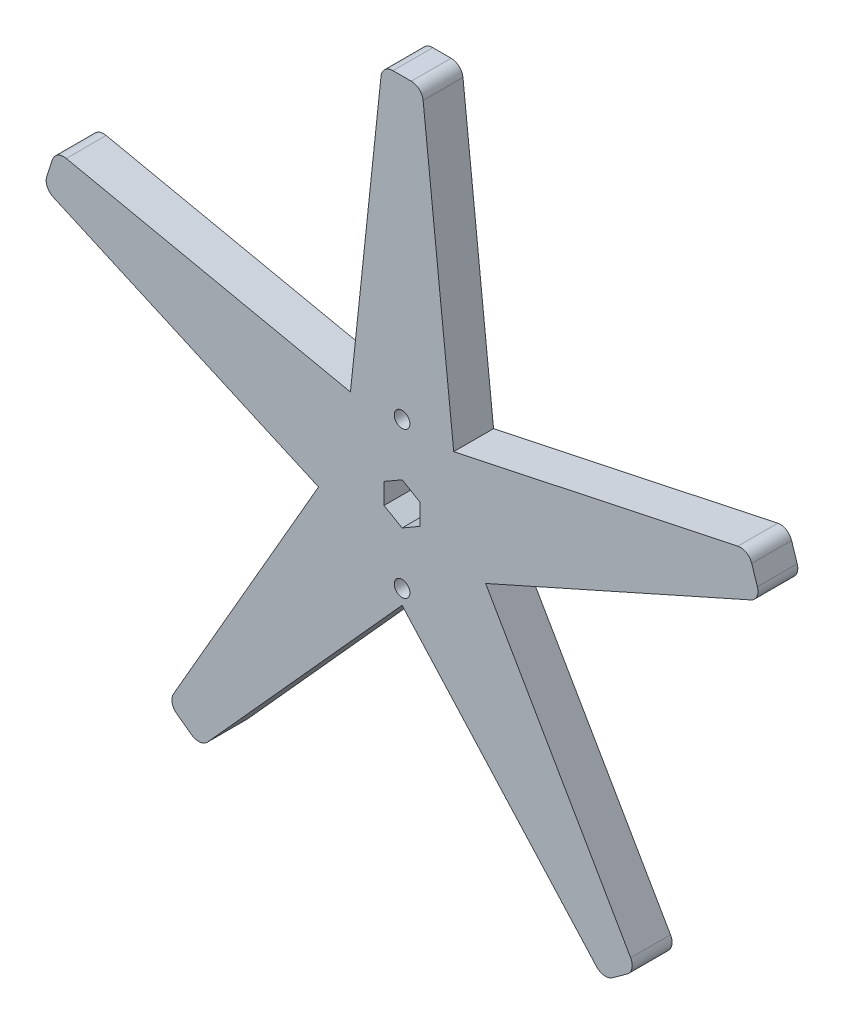
SolidWorks part; units mm, degrees
ref_plane "Front Plane" through (0, 0, 0) normal (0, 0, 1) x (1, 0, 0)
ref_plane "Top Plane" through (0, 0, 0) normal (0, 1, 0) x (1, 0, 0)
ref_plane "Right Plane" through (0, 0, 0) normal (1, 0, 0) x (0, 0, -1)
sketch "Sketch1" plane through (0, 0, 0) normal (0, 0, 1) x (1, 0, 0)
  line L0 (0, 41.9404) -> (0, 194.3404) construction
  line L1 (0, 41.9404) -> (0, 4.742) construction
  line L2 (0, 0) -> (0, 4.742) construction
  line L3 (0, 4.742) -> (0, 0) construction
  line L5 (0, -6.65) -> (5.7591, -3.325)
  line L6 (5.7591, -3.325) -> (5.7591, 3.325)
  line L7 (0, 194.3404) -> (0, 41.9404) construction
  line L8 (-2.922, 118.1404) -> (2.922, 118.1404)
  line L9 (-6.7109, 114.7315) -> (-16.458, 22.6525)
  line L10 (6.7109, 114.7315) -> (16.458, 22.6525)
  line L11 (-16.458, 22.6525) -> (0, 0) construction
  line L12 (0, 0) -> (16.458, 22.6525) construction
  line L13 (107.0424, 41.8364) -> (16.458, 22.6525)
  line L14 (111.4552, 39.2864) -> (113.2612, 33.7284)
  line L15 (111.1899, 29.0716) -> (26.6296, -8.6525)
  line L16 (72.8667, -88.8752) -> (26.6296, -8.6525)
  line L17 (71.8052, -93.8601) -> (67.0772, -97.2951)
  line L18 (62.0083, -96.7643) -> (0, -28)
  line L19 (-62.0083, -96.7643) -> (0, -28)
  line L20 (-67.0772, -97.2951) -> (-71.8052, -93.8601)
  line L21 (-72.8667, -88.8752) -> (-26.6296, -8.6525)
  line L22 (-111.1899, 29.0716) -> (-26.6296, -8.6525)
  line L23 (-113.2612, 33.7284) -> (-111.4552, 39.2864)
  line L24 (-107.0424, 41.8364) -> (-16.458, 22.6525)
  line L25 (5.7591, 3.325) -> (0, 6.65)
  line L26 (0, 6.65) -> (-5.7591, 3.325)
  line L27 (-5.7591, 3.325) -> (-5.7591, -3.325)
  line L28 (-5.7591, -3.325) -> (0, -6.65)
  circle A0 centre (0, 0) radius 28 construction
  arc A1 (6.7109, 114.7315) -> (2.922, 118.1404) centre (2.922, 114.3304) ccw
  arc A2 (-6.7109, 114.7315) -> (-2.922, 118.1404) centre (-2.922, 114.3304) cw
  arc A3 (107.0424, 41.8364) -> (111.4552, 39.2864) centre (107.8317, 38.109) cw
  arc A4 (111.1899, 29.0716) -> (113.2612, 33.7284) centre (109.6376, 32.551) ccw
  arc A5 (72.8667, -88.8752) -> (71.8052, -93.8601) centre (69.5657, -90.7777) cw
  arc A6 (62.0083, -96.7643) -> (67.0772, -97.2951) centre (64.8378, -94.2128) ccw
  arc A7 (-62.0083, -96.7643) -> (-67.0772, -97.2951) centre (-64.8378, -94.2128) cw
  arc A8 (-72.8667, -88.8752) -> (-71.8052, -93.8601) centre (-69.5657, -90.7777) ccw
  arc A9 (-111.1899, 29.0716) -> (-113.2612, 33.7284) centre (-109.6376, 32.551) cw
  arc A10 (-107.0424, 41.8364) -> (-111.4552, 39.2864) centre (-107.8317, 38.109) ccw
  circle A11 centre (0, 0) radius 5.7591 construction
  circle A12 centre (0, 23.3412) radius 2.5
  circle A13 centre (0, -23.3412) radius 2.5
  point P3 (-16.458, 22.6525)
  point P11 (0, 118.1404)
  point P16 (6.35, 118.1404)
  point P19 (-6.35, 118.1404)
  point P20 (0, 23.3412)
  point P35 (0, 0)
  point P58 (0, 0)
  dimension "D1" = 13.3
  dimension "D6" = 3.81
  dimension "D2" = 5
  dimension "D9" = 56
  dimension "D3" = 2
  dimension "D4" = 76.2
  dimension "D5" = 72
  dimension "D7" = 12.7
  dimension "D10" = 23.3412
  dimension "D8" = 5
extrude "Boss-Extrude1" add sketch "Sketch1" along normal blind 12.7
sketch "Sketch2" plane through (0, 0, 12.7) normal (0, 0, 1) x (1, 0, 0)
  circle A0 centre (0, 0) radius 28
  dimension "D1" = 56
sketch "Sketch3" plane through (0, 0, 0) normal (0, 0, -1) x (-1, 0, 0)
  circle A0 centre (0, 0) radius 28
  dimension "D1" = 56
